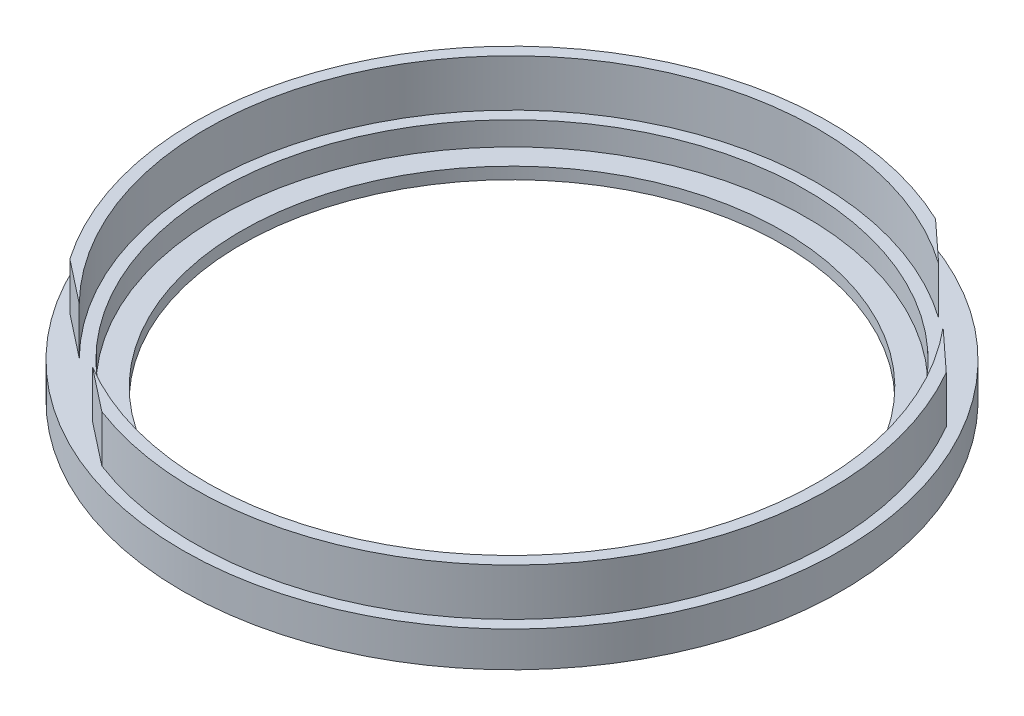
SolidWorks part; units mm, degrees
ref_plane "Plan de face" through (0, 0, 0) normal (0, 0, 1) x (1, 0, 0)
ref_plane "Plan de dessus" through (0, 0, 0) normal (0, 1, 0) x (1, 0, 0)
ref_plane "Plan de droite" through (0, 0, 0) normal (1, 0, 0) x (0, 0, -1)
sketch "Esquisse6" plane through (0, 0, 0) normal (0, 1, 0) x (1, 0, 0)
  circle A0 centre (-49.2601, 37.6293) radius 28
  dimension "D1" = 56
extrude "Boss.-Extru.3" add sketch "Esquisse6" along normal blind 3
sketch "Esquisse7" plane through (0, 3, 0) normal (0, 1, 0) x (1, 0, 0)
  circle A1 centre (-49.2601, 37.6293) radius 26
  circle A2 centre (-49.2601, 37.6293) radius 27
  circle A3 centre (-49.2601, 37.6293) radius 27
  dimension "D1" = 1
  dimension "D2" = 1
extrude "Boss.-Extru.4" add sketch "Esquisse7" along normal blind 4
sketch "Esquisse8" plane through (0, 3, 0) normal (0, 1, 0) x (1, 0, 0)
  circle A2 centre (-49.2601, 37.6293) radius 25
  circle A3 centre (-49.2601, 37.6293) radius 25
  dimension "D1" = 1
extrude "Enlèv. mat.-Extru.2" cut sketch "Esquisse8" against normal blind 2
sketch "Esquisse9" plane through (0, 1, 0) normal (0, 1, 0) x (1, 0, 0)
  circle A2 centre (-49.2601, 37.6293) radius 23
  circle A3 centre (-49.2601, 37.6293) radius 23
  dimension "D1" = 2
extrude "Enlèv. mat.-Extru.3" cut sketch "Esquisse9" against normal through all
sketch "Esquisse10" plane through (0, 7, 0) normal (0, 1, 0) x (1, 0, 0)
  line L0 (-71.4689, 22.2745) -> (-58.8789, 12.4007)
  line L1 (-71.4689, 22.2745) -> (-74.1696, 18.8308)
  line L2 (-74.1696, 18.8308) -> (-61.5796, 8.9571)
  line L3 (-61.5796, 8.9571) -> (-58.8789, 12.4007)
  line L4 (-49.2601, 37.6293) -> (-61.5796, 48.1132) construction
  line L5 (-22.9276, 54.3763) -> (-25.895, 51.1595)
  line L6 (-37.6554, 62.0081) -> (-34.688, 65.2249)
  line L7 (-37.6554, 62.0081) -> (-25.895, 51.1595)
  line L8 (-34.688, 65.2249) -> (-22.9276, 54.3763)
  circle A0 centre (-49.2601, 37.6293) radius 27 construction
  dimension "D1" = 16
extrude "Enlèv. mat.-Extru.4" cut sketch "Esquisse10" against normal blind 4
